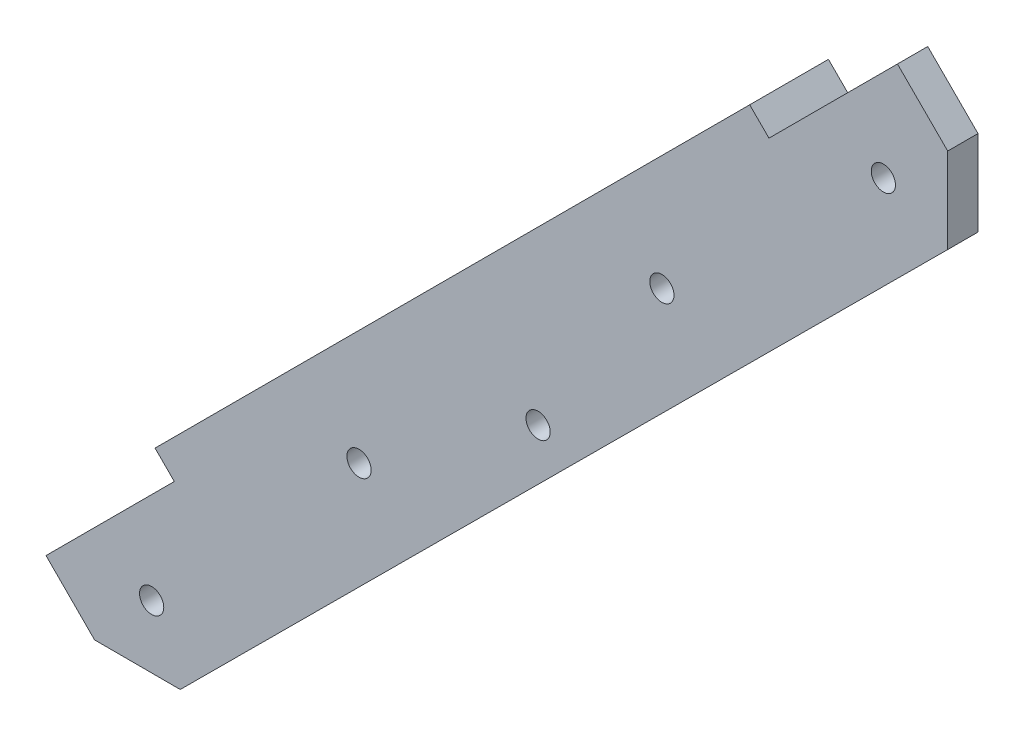
SolidWorks part; units mm, degrees
ref_plane "Front Plane" through (0, 0, 0) normal (0, 0, 1) x (1, 0, 0)
ref_plane "Top Plane" through (0, 0, 0) normal (0, 1, 0) x (1, 0, 0)
ref_plane "Right Plane" through (0, 0, 0) normal (1, 0, 0) x (0, 0, -1)
sketch "Sketch1" plane through (0, 0, 0) normal (0, 0, 1) x (1, 0, 0)
  line L0 (46.6464, 27) -> (145, 125)
  line L1 (46.6464, 27) -> (25.3951, 5.825)
  line L2 (25.3951, 5.825) -> (10.3192, 20.9553)
  line L3 (4.5, 15.136) -> (31.5052, 42.1412) construction
  line L4 (145, 125) -> (166.2514, 146.175)
  line L5 (166.2514, 146.175) -> (150.8952, 161.5312)
  line L6 (129.682, 140.318) -> (156.864, 167.5) construction
  line L7 (150.8952, 161.5312) -> (129.682, 140.318)
  line L8 (129.682, 140.318) -> (126.5, 143.5)
  line L9 (126.5, 143.5) -> (28.3232, 45.3232)
  line L10 (28.3232, 45.3232) -> (31.5052, 42.1412)
  line L11 (31.5052, 42.1412) -> (10.3192, 20.9553)
  dimension "D1" = 30
  dimension "D2" = 30
extrude "Boss-Extrude1" add sketch "Sketch1" along normal blind 5
sketch "Sketch2" plane through (0, 0, 5) normal (0, 0, 1) x (1, 0, 0)
  circle A0 centre (27.7621, 23.2569) radius 2
  circle A1 centre (148.5663, 144.0611) radius 2
  dimension "D1" = 4
  dimension "D2" = 4
extrude "Cut-Extrude1" cut sketch "Sketch2" against normal blind 15
sketch "Sketch3" plane through (0, 0, 0) normal (0, 0, -1) x (-1, 0, 0)
  line L0 (-28.3232, 45.3232) -> (-46.6134, 26.9671)
  line L1 (-25.3951, 5.825) -> (-166.2514, 146.175) construction
  line L2 (-46.6134, 26.9671) -> (-145, 125)
  line L3 (-126.5, 143.5) -> (-145, 125) construction
  line L4 (-145, 125) -> (-126.5, 143.5)
  line L5 (-126.5, 143.5) -> (-28.3232, 45.3232)
extrude "Boss-Extrude2" add sketch "Sketch3" along normal up to surface (8 mm away)
chamfer "Chamfer1" distance 10 angle 45
sketch "Sketch4" plane through (0, 0, 5) normal (0, 0, 1) x (1, 0, 0)
  circle A0 centre (62, 60) radius 2
  circle A1 centre (112, 110) radius 2
  dimension "D1" = 4
  dimension "D2" = 4
extrude "Cut-Extrude2" cut sketch "Sketch4" against normal up to next
sketch "Sketch5" plane through (0, 0, -8) normal (0, 0, -1) x (-1, 0, 0)
  circle A0 centre (-62, 60) radius 4
  circle A1 centre (-112, 110) radius 4
  dimension "D1" = 8
  dimension "D2" = 8
extrude "Cut-Extrude3" cut sketch "Sketch5" against normal blind 3
sketch "Sketch6" plane through (0, 0, -8) normal (0, 0, -1) x (-1, 0, 0)
  line L0 (-46.6134, 26.9671) -> (-145, 125) construction
  line L1 (-92.2204, 89.3678) -> (-105.6047, 85.7815)
  line L2 (-105.6047, 85.7815) -> (-109.191, 72.3972)
  line L3 (-109.191, 72.3972) -> (-99.393, 62.5993)
  line L4 (-99.393, 62.5993) -> (-86.0087, 66.1856)
  line L5 (-86.0087, 66.1856) -> (-82.4224, 79.5698)
  line L6 (-82.4224, 79.5698) -> (-92.2204, 89.3678)
  line L7 (-126.5, 143.5) -> (-28.3232, 45.3232) construction
  circle A0 centre (-95.8067, 75.9835) radius 12 construction
  dimension "D1" = 24
extrude "Cut-Extrude4" cut sketch "Sketch6" against normal blind 7
sketch "Sketch7" plane through (0, 0, -1) normal (0, 0, -1) x (-1, 0, 0)
  line L0 (-87.3214, 84.4688) -> (-91.5641, 80.2262) construction
  line L1 (-82.4224, 79.5698) -> (-92.2204, 89.3678) construction
  circle A0 centre (-91.5641, 80.2262) radius 2
  dimension "D1" = 4
  dimension "D2" = 6
extrude "Cut-Extrude5" cut sketch "Sketch7" against normal blind 17
